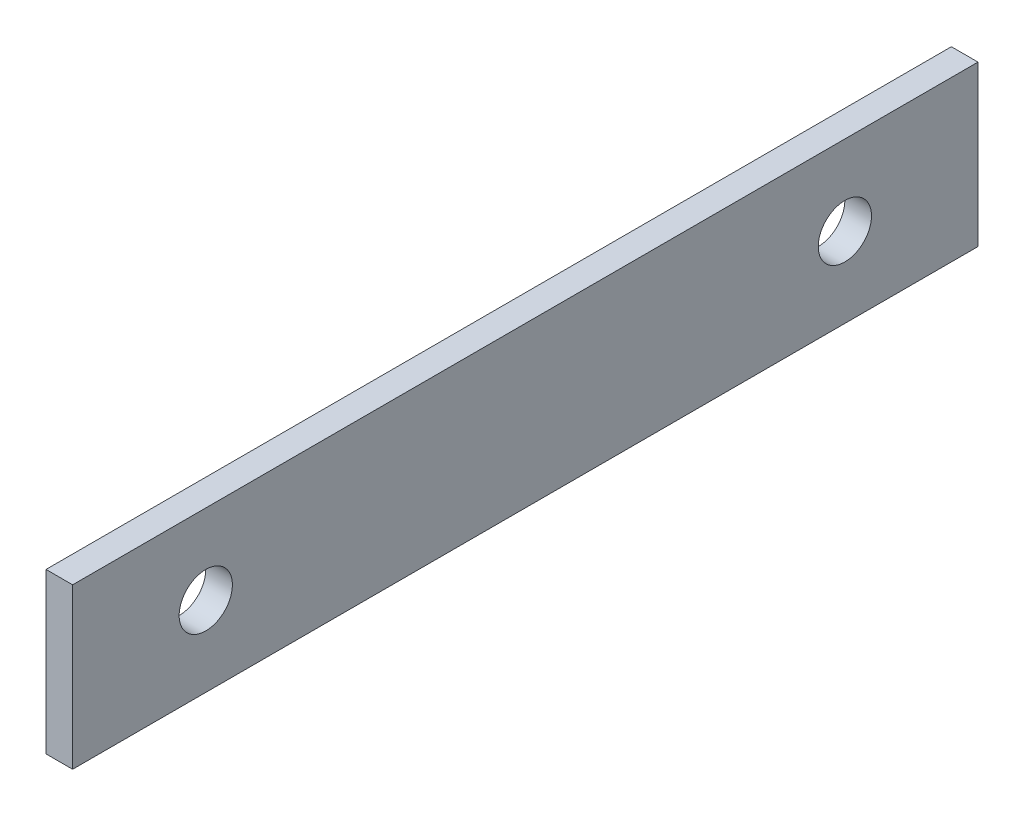
SolidWorks part; units mm, degrees
ref_plane "Front Plane" through (0, 0, 0) normal (0, 0, 1) x (1, 0, 0)
ref_plane "Top Plane" through (0, 0, 0) normal (0, 1, 0) x (1, 0, 0)
ref_plane "Right Plane" through (0, 0, 0) normal (1, 0, 0) x (0, 0, -1)
sketch "Sketch1" plane through (0, 0, 0) normal (1, 0, 0) x (0, 0, -1)
  line L1 (0, 0) -> (170, 0)
  line L2 (0, 0) -> (0, 30)
  line L3 (0, 30) -> (170, 30)
  line L4 (170, 0) -> (170, 30)
  circle A0 centre (25, 15) radius 5
  circle A1 centre (145, 15) radius 5
  dimension "D5" = 10
  dimension "D6" = 10
  dimension "D1" = 170
  dimension "D2" = 30
  dimension "D3" = 25
  dimension "D4" = 145
  dimension "D7" = 15
  dimension "D8" = 15
extrude "Boss-Extrude1" add sketch "Sketch1" along normal blind 5
